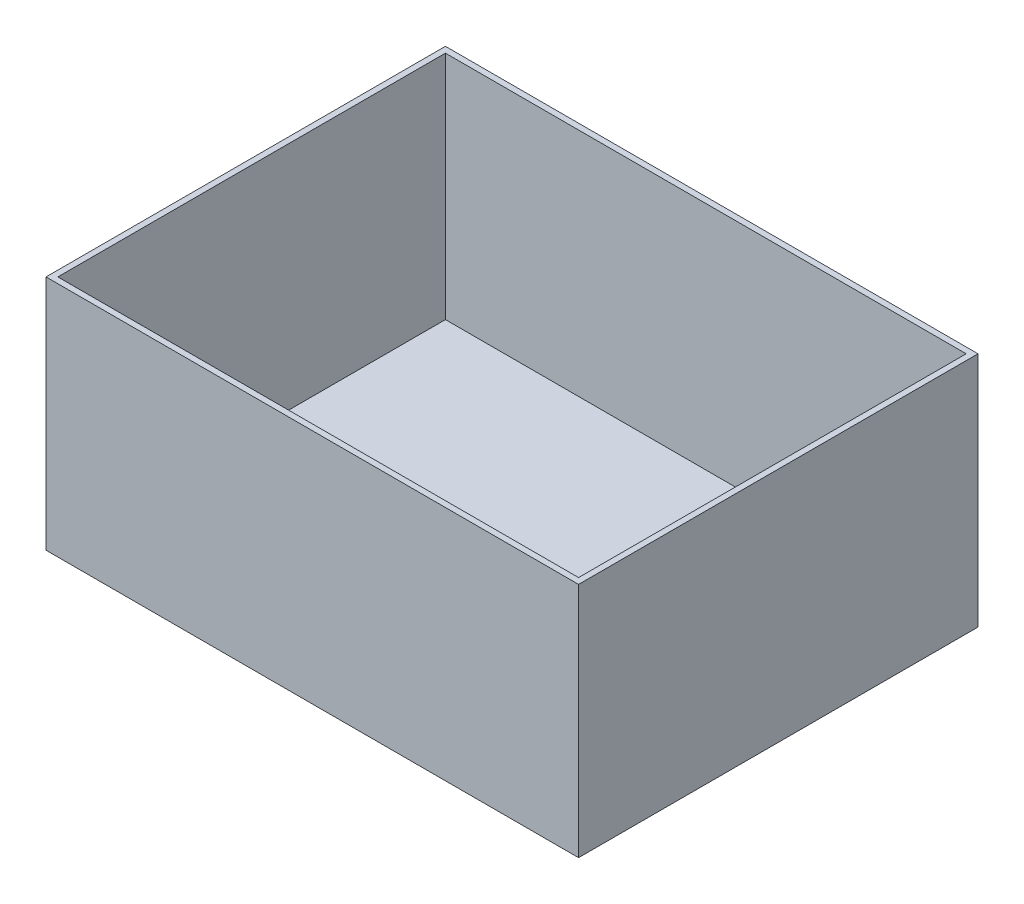
SolidWorks part; units mm, degrees
ref_plane "Front Plane" through (0, 0, 0) normal (0, 0, 1) x (1, 0, 0)
ref_plane "Top Plane" through (0, 0, 0) normal (0, 1, 0) x (1, 0, 0)
ref_plane "Right Plane" through (0, 0, 0) normal (1, 0, 0) x (0, 0, -1)
sketch "Sketch1" plane through (0, 0, 0) normal (0, 0, 1) x (1, 0, 0)
  line L1 (0, 0) -> (-900, 0)
  line L2 (0, 0) -> (0, 400)
  line L3 (0, 400) -> (-900, 400)
  line L4 (-900, 0) -> (-900, 400)
  dimension "D1" = 400
  dimension "D2" = 900
extrude "Boss-Extrude1" add sketch "Sketch1" along normal blind 675
shell "Shell1" thickness 10
ref_plane "Plane1" through (0, 0, 0) normal (0, -1, 0) x (-1, 0, 0)
sketch "Sketch3" plane through (0, 0, 0) normal (0, -1, 0) x (-1, 0, 0)
  line L0 (300, -235) -> (250, -235)
  line L1 (300, -450) -> (250, -450)
  line L2 (300, -450) -> (300, -440)
  line L3 (300, -440) -> (250, -440)
  line L4 (250, -450) -> (250, -440)
  line L5 (300, -235) -> (300, -225)
  line L6 (300, -225) -> (250, -225)
  line L7 (250, -235) -> (250, -225)
  line L8 (900, 0) -> (0, 0) construction
  line L9 (0, -675) -> (0, 0) construction
  line L20 (900, -675) -> (0, -675) construction
  line L21 (300, -20) -> (250, -20) [skipped]
  line L22 (300, -10) -> (250, -10) [skipped]
  line L23 (250, -20) -> (250, -10) [skipped]
  line L24 (300, -20) -> (300, -10) [skipped]
  line L25 (300, 195) -> (250, 195) [skipped]
  line L26 (300, 205) -> (250, 205) [skipped]
  line L27 (250, 195) -> (250, 205) [skipped]
  line L28 (300, 195) -> (300, 205) [skipped]
  line L29 (300, 410) -> (250, 410) [skipped]
  line L30 (300, 420) -> (250, 420) [skipped]
  line L31 (250, 410) -> (250, 420) [skipped]
  line L32 (300, 410) -> (300, 420) [skipped]
  dimension "D1" = 10
  dimension "D2" = 50
  dimension "D4" = 225
  dimension "D5" = 205
  dimension "D6" = 225
  dimension "D7" = 250
  dimension "D3" = 5
extrude "Boss-Extrude4" add sketch "Sketch3" along normal blind 50
